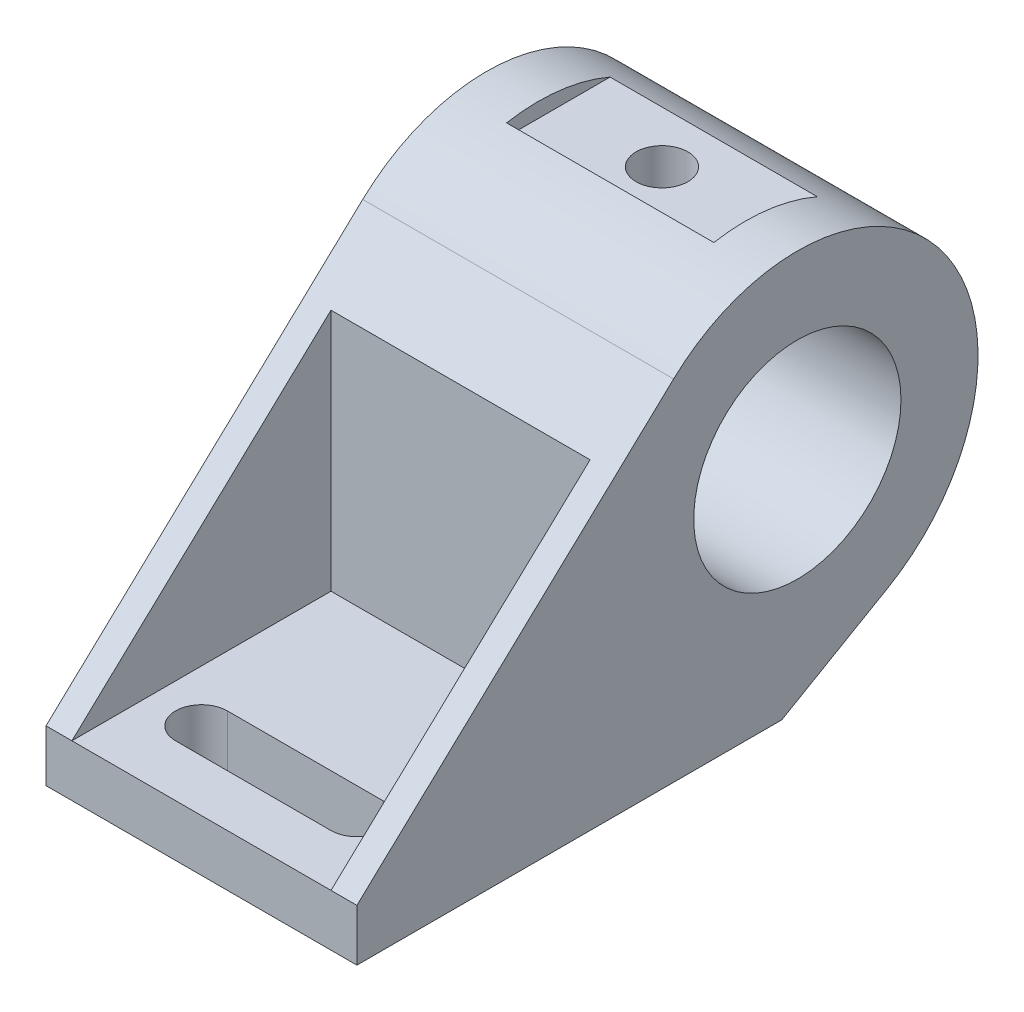
SolidWorks part; units mm, degrees
ref_plane "Front Plane" through (0, 0, 0) normal (0, 0, 1) x (1, 0, 0)
ref_plane "Top Plane" through (0, 0, 0) normal (0, 1, 0) x (1, 0, 0)
ref_plane "Right Plane" through (0, 0, 0) normal (1, 0, 0) x (0, 0, -1)
sketch "Sketch2" plane through (0, 0, 0) normal (0, 1, 0) x (1, 0, 0)
  line L1 (-30, -41) -> (30, -41)
  line L2 (-30, -41) -> (-30, 41)
  line L3 (-30, 41) -> (30, 41)
  line L4 (30, -41) -> (30, 41)
  line L5 (-30, -41) -> (30, 41) construction
  line L6 (-30, 41) -> (30, -41) construction
  point P0 (0, 0)
  dimension "D1" = 60
  dimension "D2" = 82
extrude "Boss-Extrude2" add sketch "Sketch2" along normal blind 10
sketch "Sketch4" plane through (30, 0, 0) normal (1, 0, 0) x (0, 0, -1)
  line L3 (41, 10) -> (-41, 10)
  line L4 (41, 0) -> (61.4365, 11.799)
  line L5 (-41, 0) -> (41, 0) construction
  line L6 (41, 10) -> (41, 0)
  line L7 (-41, 10) -> (20.1236, 67.4175)
  line L8 (-41, 10) -> (41, 10)
  line L9 (41, 0) -> (81.6388, 0) construction
  circle A0 centre (44, 42) radius 20
  arc A1 (61.4365, 11.799) -> (20.1236, 67.4175) centre (44, 42) ccw
  arc A2 (61.4365, 11.799) -> (20.1236, 67.4175) centre (44, 42) ccw
  dimension "D1" = 85
  dimension "D3" = 30
extrude "Boss-Extrude3" add sketch "Sketch4" against normal through all
ref_plane "Plane2" through (0, 60, 0) normal (0, 1, 0) x (1, 0, 0)
sketch "Sketch8" plane through (0, 60, 0) normal (0, 1, 0) x (1, 0, 0)
  line L0 (-30, -41) -> (30, -41) construction
  line L1 (-25, -41) -> (25, -41)
  line L2 (-25, -41) -> (-25, 9)
  line L3 (-25, 9) -> (25, 9)
  line L4 (25, -41) -> (25, 9)
  line L5 (-30, -41) -> (-30, 20.1236) construction
  line L6 (30, -41) -> (30, 20.1236) construction
  dimension "D1" = 5
  dimension "D2" = 5
  dimension "D3" = 50
extrude "Cut-Extrude1" cut sketch "Sketch8" against normal blind 50
sketch "Sketch9" plane through (0, 10, 0) normal (0, 1, 0) x (1, 0, 0)
  line L0 (-15, -26) -> (15, -26) construction
  line L1 (-15, -21) -> (15, -21)
  line L2 (-15, -31) -> (15, -31)
  line L3 (-25, -41) -> (25, -41) construction
  line L4 (25, 9) -> (-25, 9) construction
  arc A0 (-15, -21) -> (-15, -31) centre (-15, -26) ccw
  arc A1 (15, -31) -> (15, -21) centre (15, -26) ccw
  point P2 (0, -26)
  point P11 (0, 0)
  dimension "D3" = 30
  dimension "D1" = 10
  dimension "D2" = 30
ref_plane "Plane3" through (0, 77, 0) normal (0, 1, 0) x (1, 0, 0)
extrude "Cut-Extrude2" cut sketch "Sketch9" against normal blind 50
sketch "Sketch14" plane through (0, 77, 0) normal (0, 1, 0) x (1, 0, 0)
  line L1 (-20, 37.8885) -> (20, 37.8885)
  line L2 (-20, 37.8885) -> (-20, 61.1082)
  line L3 (-20, 61.1082) -> (20, 61.1082)
  line L4 (20, 37.8885) -> (20, 61.1082)
  line L5 (-20, 37.8885) -> (20, 61.1082) construction
  line L6 (-20, 61.1082) -> (20, 37.8885) construction
  point P0 (0, 49.4984)
  point P5 (0, 0)
  dimension "D1" = 40
extrude "Cut-Extrude3" cut sketch "Sketch14" against normal blind 3
sketch "Sketch15" plane through (0, 74, 0) normal (0, 1, 0) x (1, 0, 0)
  circle A0 centre (0, 47.8748) radius 5
  dimension "D1" = 10
extrude "Cut-Extrude4" cut sketch "Sketch15" against normal up to next
